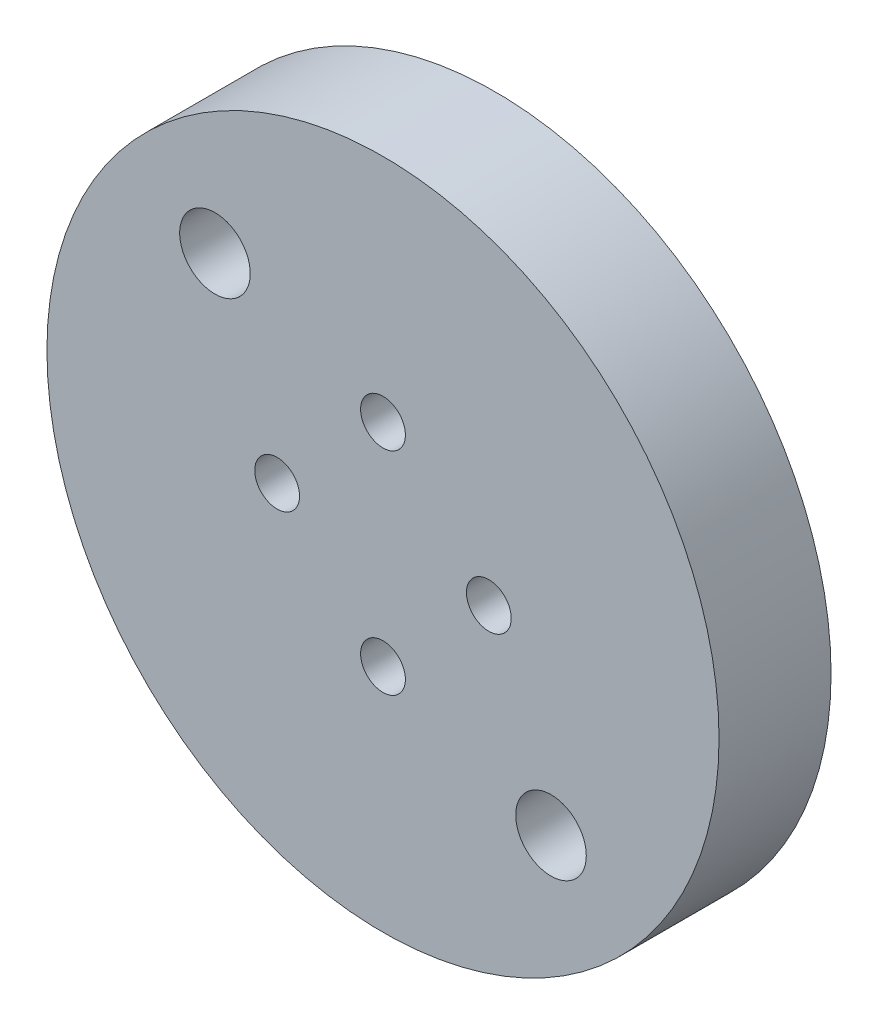
SolidWorks part; units mm, degrees
ref_plane "Front Plane" through (0, 0, 0) normal (0, 0, 1) x (1, 0, 0)
ref_plane "Top Plane" through (0, 0, 0) normal (0, 1, 0) x (1, 0, 0)
ref_plane "Right Plane" through (0, 0, 0) normal (1, 0, 0) x (0, 0, -1)
sketch "Sketch1" plane through (0, 0, 0) normal (0, 0, 1) x (1, 0, 0)
  line L0 (-169.7289, -38.1) -> (169.7289, -38.1) construction
  line L1 (-110.0162, 38.1) -> (110.0162, 38.1) construction
  circle A0 centre (0, 0) radius 38.1
  circle A2 centre (12, 0) radius 2.54
  circle A6 centre (0, -12) radius 2.54
  circle A7 centre (-12, 0) radius 2.54
  circle A8 centre (0, 12) radius 2.54
  point P7 (0, -38.1)
  point P14 (0, 38.1)
  point P22 (0, 0)
  dimension "D1" = 76.2
  dimension "D2" = 5.08
  dimension "D5" = 12
  dimension "D6" = 4
extrude "Boss-Extrude1" add sketch "Sketch1" along normal blind 12.7
sketch "Sketch2" plane through (0, 0, 0) normal (0, 0, 1) x (1, 0, 0)
  circle A3 centre (19.05, -19.05) radius 4
  dimension "D1" = 8
  dimension "D2" = 19.05
  dimension "D3" = 19.05
extrude "Cut-Extrude1" cut sketch "Sketch2" along normal through all
sketch "Sketch3" plane through (0, 0, 0) normal (0, 0, 1) x (1, 0, 0)
  circle A0 centre (19.05, -19.05) radius 9.525
  dimension "D1" = 19.05
extrude "Cut-Extrude2" cut sketch "Sketch3" along normal blind 6.35
sketch "Sketch4" plane through (0, 0, 0) normal (0, 0, 1) x (1, 0, 0)
  circle A0 centre (-19.05, 19.05) radius 4
  dimension "D3" = 8
  dimension "D1" = 19.05
  dimension "D2" = 19.05
extrude "Cut-Extrude3" cut sketch "Sketch4" along normal through all
sketch "Sketch5" plane through (0, 0, 0) normal (0, 0, 1) x (1, 0, 0)
  circle A0 centre (-19.05, 19.05) radius 9.525
  dimension "D1" = 19.05
extrude "Cut-Extrude5" cut sketch "Sketch5" along normal blind 6.35
